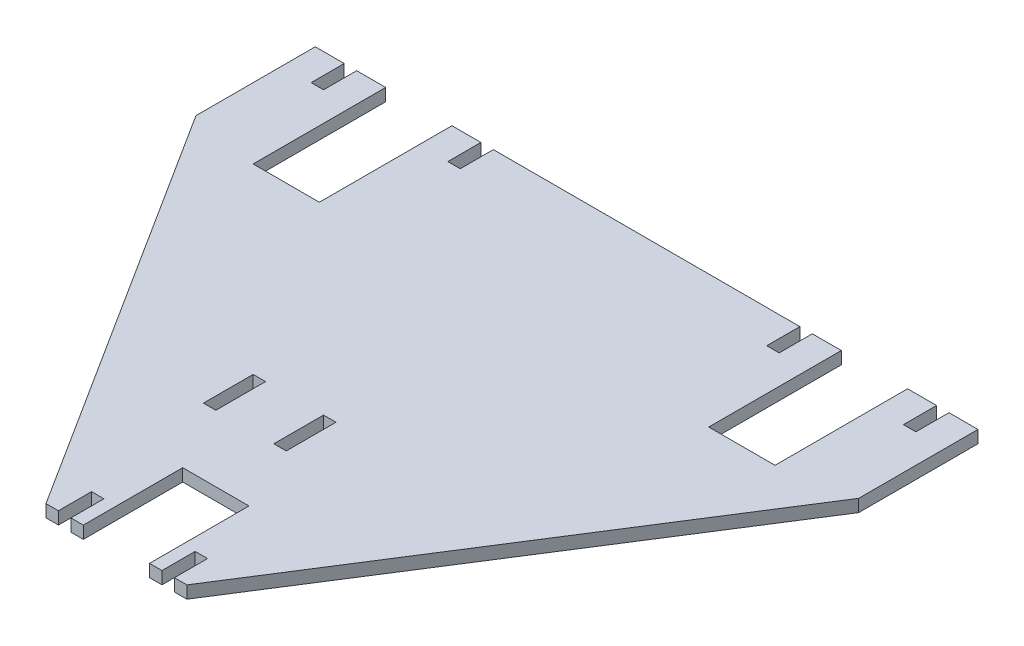
SolidWorks part; units mm, degrees
ref_plane "Front Plane" through (0, 0, 0) normal (0, 0, 1) x (1, 0, 0)
ref_plane "Top Plane" through (0, 0, 0) normal (0, 1, 0) x (1, 0, 0)
ref_plane "Right Plane" through (0, 0, 0) normal (1, 0, 0) x (0, 0, -1)
sketch "Sketch1" plane through (0, 0, 0) normal (0, 1, 0) x (1, 0, 0)
  line L0 (0, 0) -> (0, -142.875) construction
  line L1 (12.7, -63.5) -> (-12.7, -63.5)
  line L2 (-12.7, -63.5) -> (-12.7, -101.6)
  line L3 (-12.7, -101.6) -> (-17.4625, -101.6)
  line L4 (-26.9875, -101.6) -> (-127, 55.88)
  line L5 (-127, 55.88) -> (-127, 101.6)
  line L6 (-127, 101.6) -> (-115.8875, 101.6)
  line L7 (-100.0125, 101.6) -> (-100.0125, 50.8)
  line L9 (-100.0125, 50.8) -> (-74.6125, 50.8)
  line L10 (-74.6125, 50.8) -> (-74.6125, 101.6)
  line L11 (-74.6125, 101.6) -> (-63.5, 101.6)
  line L13 (74.6125, 50.8) -> (74.6125, 101.6)
  line L14 (100.0125, 50.8) -> (74.6125, 50.8)
  line L15 (100.0125, 101.6) -> (100.0125, 50.8)
  line L16 (127, 101.6) -> (115.8875, 101.6)
  line L17 (127, 55.88) -> (127, 101.6)
  line L18 (26.9875, -101.6) -> (127, 55.88)
  line L19 (12.7, -101.6) -> (17.4625, -101.6)
  line L20 (12.7, -63.5) -> (12.7, -101.6)
  line L21 (-127, 101.6) -> (127, -101.6) construction
  line L22 (-22.225, -101.6) -> (-26.9875, -101.6)
  line L24 (-22.225, -101.6) -> (-22.225, -88.9)
  line L25 (-22.225, -88.9) -> (-17.4625, -88.9)
  line L26 (-17.4625, -101.6) -> (-17.4625, -88.9)
  line L27 (22.225, -101.6) -> (22.225, -88.9)
  line L28 (22.225, -88.9) -> (17.4625, -88.9)
  line L29 (17.4625, -101.6) -> (17.4625, -88.9)
  line L30 (22.225, -101.6) -> (26.9875, -101.6)
  line L31 (-87.3125, 50.8) -> (-87.3125, 101.6) construction
  line L32 (-111.125, 101.6) -> (-100.0125, 101.6)
  line L34 (-115.8875, 101.6) -> (-115.8875, 88.9)
  line L35 (-115.8875, 88.9) -> (-111.125, 88.9)
  line L36 (-111.125, 101.6) -> (-111.125, 88.9)
  line L37 (-58.7375, 101.6) -> (-58.7375, 88.9)
  line L38 (-58.7375, 88.9) -> (-63.5, 88.9)
  line L39 (-63.5, 101.6) -> (-63.5, 88.9)
  line L40 (-58.7375, 101.6) -> (58.7375, 101.6)
  line L41 (115.8875, 101.6) -> (115.8875, 88.9)
  line L42 (115.8875, 88.9) -> (111.125, 88.9)
  line L43 (111.125, 101.6) -> (111.125, 88.9)
  line L44 (58.7375, 101.6) -> (58.7375, 88.9)
  line L45 (63.5, 101.6) -> (63.5, 88.9)
  line L46 (58.7375, 88.9) -> (63.5, 88.9)
  line L47 (63.5, 101.6) -> (74.6125, 101.6)
  line L48 (111.125, 101.6) -> (100.0125, 101.6)
  point P26 (0, -63.5)
  dimension "D2" = 25.4
  dimension "D3" = 254
  dimension "D5" = 38.1
  dimension "D6" = 50.8
  dimension "D7" = 203.2
  dimension "D8" = 45.72
  dimension "D9" = 26.9875
  dimension "D4" = 14.2875
  dimension "D10" = 4.7625
  dimension "D11" = 12.7
  dimension "D12" = 4.7625
extrude "Boss-Extrude1" add sketch "Sketch1" along normal blind 4.7625 contours L13 L47 L45 L46 L44 L40 L37 L38 L39 L11 L10 L9 L7 L32 L36 L35 L34 L6 L5 L4 L22 L24 L25 L26 L3 L2 L1 L20 L19 L29 L28 L27 L30 L18 L17 L16 L41 L42 L43 L48 L15 L14
sketch "Sketch2" plane through (0, 4.7625, 0) normal (0, 1, 0) x (1, 0, 0)
  line L0 (-14.2875, 0) -> (-14.2875, 54.8341) construction
  line L6 (-58.7375, 88.9) -> (-63.5, 88.9) construction
  line L7 (-30.1625, -19.05) -> (-25.4, -19.05)
  line L8 (-30.1625, -19.05) -> (-30.1625, -38.1)
  line L9 (-30.1625, -38.1) -> (-25.4, -38.1)
  line L10 (-25.4, -19.05) -> (-25.4, -38.1)
  line L12 (-3.175, -19.05) -> (-3.175, -38.1)
  line L13 (1.5875, -38.1) -> (-3.175, -38.1)
  line L14 (1.5875, -19.05) -> (1.5875, -38.1)
  line L15 (1.5875, -19.05) -> (-3.175, -19.05)
  line L17 (12.7, -63.5) -> (-12.7, -63.5) construction
  point P11 (-11.1125, -7.6745)
  dimension "D2" = 25.4
  dimension "D4" = 14.2875
  dimension "D3" = 31.75
  dimension "D1" = 19.05
extrude "Cut-Extrude1" cut sketch "Sketch2" against normal through all
equation "\"D1@Boss-Extrude1\"=\"thick@FullAssem.Assembly\""
equation "\"D4@Sketch1\"=\"thick@FullAssem.Assembly\"*3"
equation "\"D10@Sketch1\"=\"thick@FullAssem.Assembly\""
equation "\"D9@Sketch1\"=\"thick@FullAssem.Assembly\"*3+0.5"
equation "\"D12@Sketch1\"=\"thick@FullAssem.Assembly\""
equation "\"D3@Sketch2\"=\"MotorLength@Motor-1.Part\""
equation "\"D1@Sketch2\" =  ( \"MotorDiameter@Motor<1>.Part\" + 0.5 )  / 2"
equation "\"D4@Sketch2\"=-3*\"thick@FullAssem.Assembly\""
